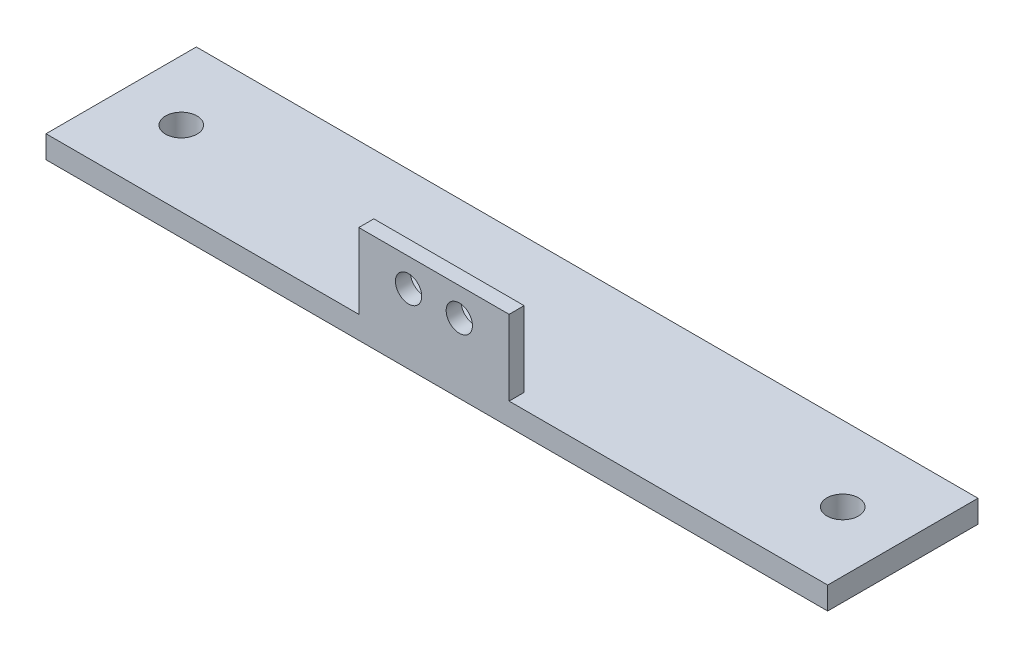
SolidWorks part; units mm, degrees
ref_plane "Plan de face" through (0, 0, 0) normal (0, 0, 1) x (1, 0, 0)
ref_plane "Plan de dessus" through (0, 0, 0) normal (0, 1, 0) x (1, 0, 0)
ref_plane "Plan de droite" through (0, 0, 0) normal (1, 0, 0) x (0, 0, -1)
sketch "Esquisse1" plane through (0, 0, 0) normal (0, 1, 0) x (1, 0, 0)
  line L0 (-51.7913, 20.165) -> (52.2087, 20.165)
  line L1 (-51.7913, 20.165) -> (-51.7913, 0.165)
  line L2 (52.2087, 20.165) -> (52.2087, 0.165)
  line L3 (-51.7913, 0.165) -> (52.2087, 0.165)
  line L4 (-51.7913, 10.165) -> (-43.7913, 10.165)
  line L5 (52.2087, 10.165) -> (44.2087, 10.165)
  circle A0 centre (-43.7913, 10.165) radius 2.1
  circle A1 centre (44.2087, 10.165) radius 2.1
  dimension "D1" = 104
  dimension "D2" = 20
extrude "Boss.-Extru.1" add sketch "Esquisse1" along normal blind 3
sketch "Esquisse2" plane through (0, 3, 0) normal (0, 1, 0) x (1, 0, 0)
  line L0 (-0.1779, 0.165) -> (-10.1779, 0.165)
  line L1 (-0.1779, 0.165) -> (9.8221, 0.165)
  line L2 (-51.7913, 0.165) -> (52.2087, 0.165) construction
  line L3 (-10.1779, 0.165) -> (-10.1779, 2.165)
  line L4 (-10.1779, 2.165) -> (9.8221, 2.165)
  line L5 (9.8221, 2.165) -> (9.8221, 0.165)
  dimension "D1" = 10
  dimension "D2" = 10
extrude "Boss.-Extru.2" add sketch "Esquisse2" along normal blind 10
sketch "Esquisse3" plane through (0, 0, -0.165) normal (0, 0, 1) x (1, 0, 0)
  line L0 (-0.1779, 13) -> (1.4471, 13)
  line L1 (-10.1779, 13) -> (9.8221, 13) construction
  line L2 (-0.1779, 13) -> (-1.8029, 13)
  line L3 (1.4471, 13) -> (4.9471, 13)
  line L4 (-1.8029, 13) -> (-5.3029, 13)
  line L5 (-3.5529, 13) -> (-3.5529, 9.25)
  line L6 (3.1971, 13) -> (3.1971, 9.25)
  circle A0 centre (-3.5529, 9.25) radius 1.75
  circle A1 centre (3.1971, 9.25) radius 1.75
  dimension "D1" = 1.625
  dimension "D2" = 1.625
extrude "Enlèv. mat.-Extru.1" cut sketch "Esquisse3" against normal blind 10
